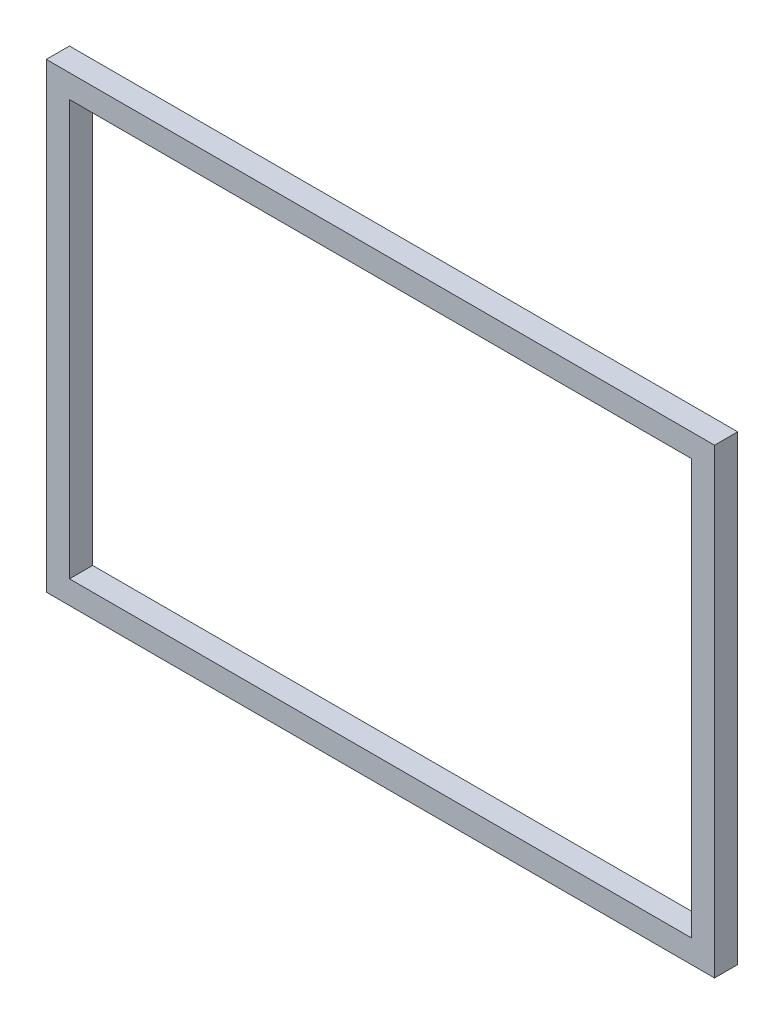
SolidWorks part; units mm, degrees
ref_plane "Front Plane" through (0, 0, 0) normal (0, 0, 1) x (1, 0, 0)
ref_plane "Top Plane" through (0, 0, 0) normal (0, 1, 0) x (1, 0, 0)
ref_plane "Right Plane" through (0, 0, 0) normal (1, 0, 0) x (0, 0, -1)
sketch "Sketch1" plane through (0, 0, 0) normal (0, 0, 1) x (1, 0, 0)
  line L0 (-10.5, -50.54) -> (-10.5, -56.34)
  line L1 (-42.61, -28.44) -> (42.61, -28.44)
  line L2 (-42.61, -28.44) -> (-42.61, 28.44)
  line L3 (-42.61, 28.44) -> (42.61, 28.44)
  line L4 (42.61, -28.44) -> (42.61, 28.44)
  line L5 (-42.61, -28.44) -> (42.61, 28.44) construction
  line L6 (-42.61, 28.44) -> (42.61, -28.44) construction
  line L7 (-62.61, 48.44) -> (62.61, 48.44)
  line L8 (-62.61, 48.44) -> (-62.61, -68.44)
  line L9 (-62.61, -68.44) -> (62.61, -68.44)
  line L10 (62.61, 48.44) -> (62.61, -68.44)
  line L11 (-25.5, -50.54) -> (-19.5, -50.54)
  line L12 (-25.5, -50.54) -> (-25.5, -56.34)
  line L13 (-25.5, -56.34) -> (-19.5, -56.34)
  line L14 (-19.5, -50.54) -> (-19.5, -56.34)
  line L15 (-47.61, -53.44) -> (47.61, -53.44) construction
  line L16 (-10.5, -50.54) -> (-4.5, -50.54)
  line L17 (-4.5, -50.54) -> (-4.5, -56.34)
  line L18 (-10.5, -56.34) -> (-4.5, -56.34)
  line L19 (4.5, -50.54) -> (4.5, -56.34)
  line L20 (4.5, -50.54) -> (10.5, -50.54)
  line L21 (10.5, -50.54) -> (10.5, -56.34)
  line L22 (4.5, -56.34) -> (10.5, -56.34)
  line L23 (19.5, -50.54) -> (19.5, -56.34)
  line L24 (19.5, -50.54) -> (25.5, -50.54)
  line L25 (25.5, -50.54) -> (25.5, -56.34)
  line L26 (19.5, -56.34) -> (25.5, -56.34)
  line L27 (-4.5, -53.44) -> (4.5, -53.44) construction
  line L28 (0, -68.44) -> (0, -53.44) construction
  line L29 (-4.5, -53.44) -> (4.5, -53.44) construction
  line L31 (45.785, -31.615) -> (-45.785, -31.615)
  line L32 (45.785, -31.615) -> (45.785, 31.615)
  line L33 (45.785, 31.615) -> (-45.785, 31.615)
  line L34 (-45.785, -31.615) -> (-45.785, 31.615)
  line L35 (45.785, -31.615) -> (-45.785, 31.615) construction
  line L36 (45.785, 31.615) -> (-45.785, -31.615) construction
  circle A0 centre (-47.61, -53.44) radius 8.5
  circle A1 centre (47.61, -53.44) radius 8.5
  point P0 (0, 0)
  point P16 (-25.5, -53.44)
  point P35 (0, 0)
  dimension "D12" = 17
  dimension "D13" = 17
  dimension "D1" = 56.88
  dimension "D2" = 85.22
  dimension "D3" = 20
  dimension "D4" = 20
  dimension "D5" = 125.22
  dimension "D6" = 20
  dimension "D7" = 40
  dimension "D8" = 15
  dimension "D9" = 15
  dimension "D10" = 15
  dimension "D11" = 15
  dimension "D14" = 6
  dimension "D15" = 5.8
  dimension "D17" = 3.175
  dimension "D18" = 3.175
  dimension "D16" = 4
extrude "Boss-Extrude1" add sketch "Sketch1" along normal blind 3.175 contours L32 L31 L34 L33 | L2 L1 L4 L3
